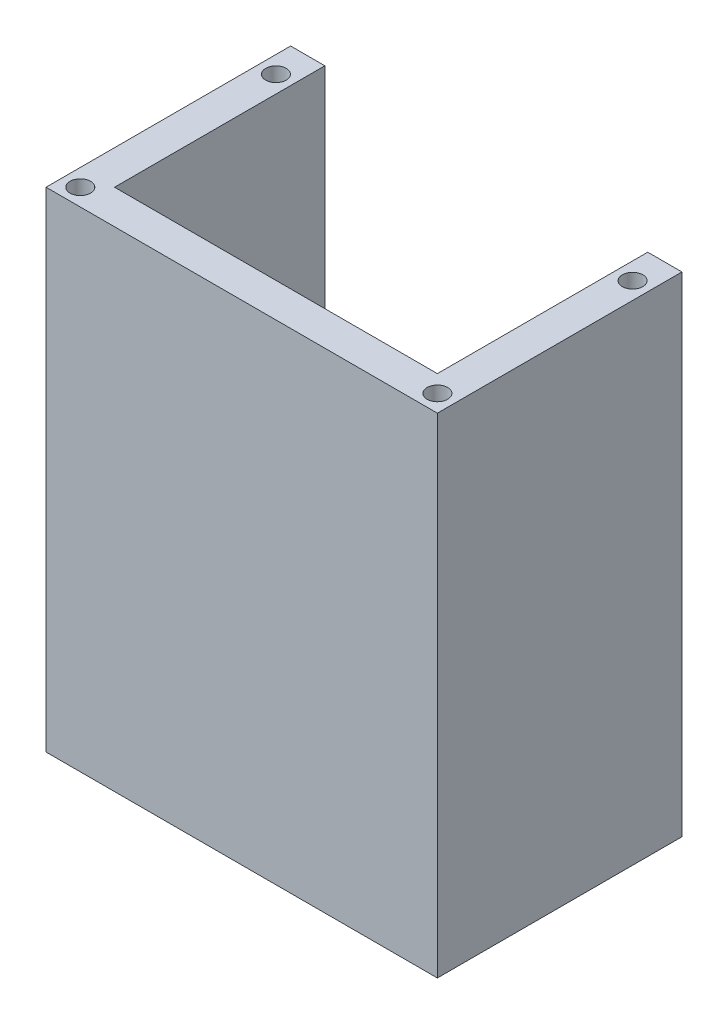
SolidWorks part; units mm, degrees
ref_plane "前基準面" through (0, 0, 0) normal (0, 0, 1) x (1, 0, 0)
ref_plane "上基準面" through (0, 0, 0) normal (0, 1, 0) x (1, 0, 0)
ref_plane "右基準面" through (0, 0, 0) normal (1, 0, 0) x (0, 0, -1)
sketch "草圖1" plane through (0, 0, 0) normal (0, 1, 0) x (1, 0, 0)
  line L1 (0, 0) -> (80, 0)
  line L2 (0, 0) -> (0, 50)
  line L3 (0, 50) -> (80, 50)
  line L4 (80, 0) -> (80, 50)
extrude "填料-伸長1" add sketch "草圖1" along normal blind 100
sketch "草圖3" plane through (0, 0, 0) normal (0, 1, 0) x (1, 0, 0)
  line L1 (7, 7) -> (73, 7)
  line L2 (7, 7) -> (7, 51.4698)
  line L3 (7, 51.4698) -> (73, 51.4698)
  line L4 (73, 7) -> (73, 51.4698)
extrude "除料-伸長1" cut sketch "草圖3" along normal through all
sketch "草圖4" plane through (0, 0, 0) normal (0, 1, 0) x (1, 0, 0)
  circle A0 centre (3.5, 3.5) radius 2.1
  circle A1 centre (3.5, 43.5) radius 2.1
  circle A2 centre (76.5, 43.4) radius 2.1
  circle A3 centre (76.5, 3.5) radius 2.1
extrude "除料-伸長2" cut sketch "草圖4" along normal through all
